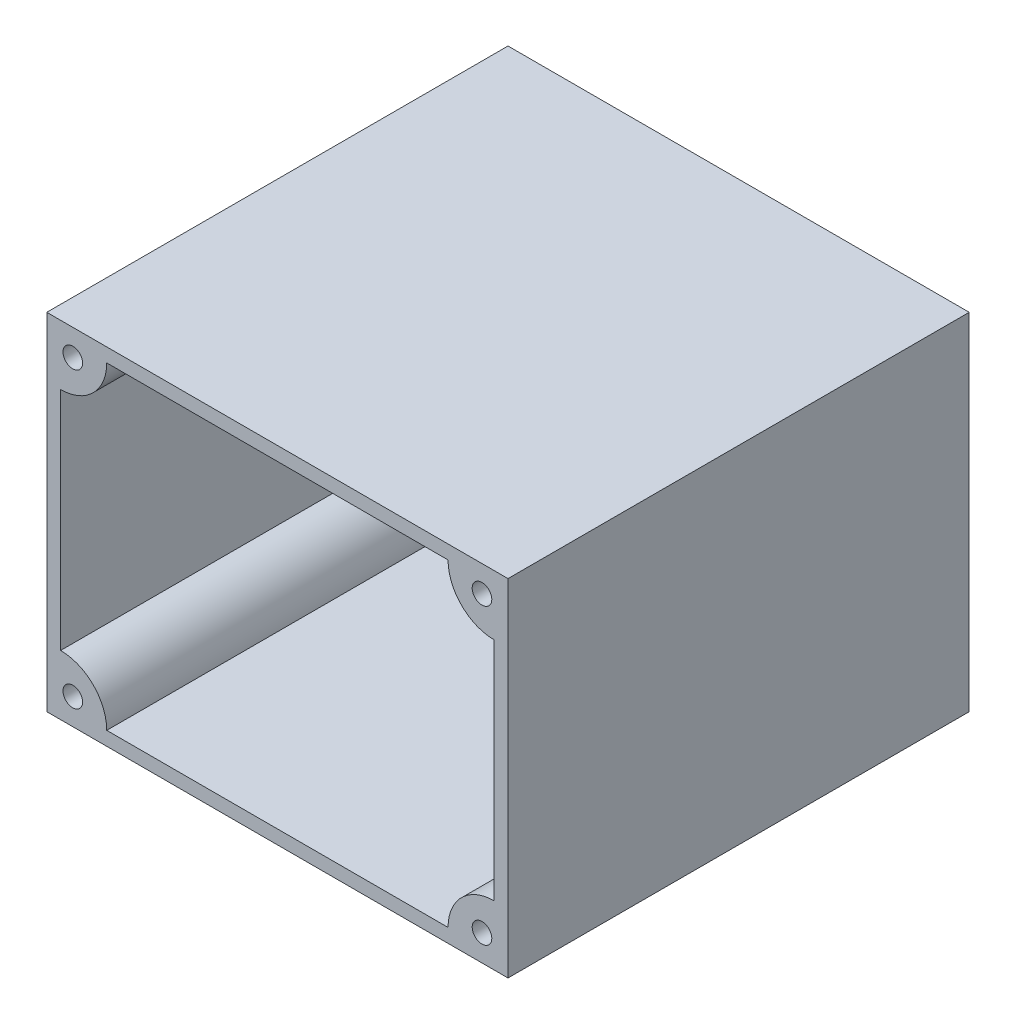
SolidWorks part; units mm, degrees
ref_plane "Plan de face" through (0, 0, 0) normal (0, 0, 1) x (1, 0, 0)
ref_plane "Plan de dessus" through (0, 0, 0) normal (0, 1, 0) x (1, 0, 0)
ref_plane "Plan de droite" through (0, 0, 0) normal (1, 0, 0) x (0, 0, -1)
sketch "Esquisse1" plane through (0, 0, 0) normal (0, 0, 1) x (1, 0, 0)
  line L1 (-40, 30) -> (40, 30)
  line L2 (-40, 30) -> (-40, -30)
  line L3 (-40, -30) -> (40, -30)
  line L4 (40, 30) -> (40, -30)
  line L5 (-40, 30) -> (40, -30) construction
  line L6 (-40, -30) -> (40, 30) construction
  point P0 (0, 0)
  dimension "D1" = 80
  dimension "D2" = 60
extrude "Boss.-Extru.1" add sketch "Esquisse1" along normal blind 80
shell "Coque1" thickness 2.4
sketch "Esquisse2" plane through (0, 0, 80) normal (0, 0, 1) x (1, 0, 0)
  line L0 (-37.6, 27.6) -> (-37.6, 19.6)
  line L1 (-37.6, 27.6) -> (-37.6, -27.6) construction
  line L2 (37.6, 27.6) -> (-37.6, 27.6) construction
  line L3 (-29.6, 27.6) -> (-37.6, 27.6)
  arc A0 (-37.6, 19.6) -> (-29.6, 27.6) centre (-37.6, 27.6) ccw
  dimension "D1" = 8
extrude "Boss.-Extru.2" add sketch "Esquisse2" against normal up to next
hole_wizard "Dégagement M31" positions "Esquisse3" profile "Esquisse4" hole size "M3" standard "ISO"
sketch "Esquisse3" plane through (0, 0, 80) normal (0, 0, 1) x (1, 0, 0)
  point P0 (-35.4882, 25.4607)
sketch "Esquisse4" plane through (-35.4882, 25.4607, 80) normal (1, 0, 0) x (0, -1, 0)
  line L0 (0, 0) -> (0, 11.0215)
  line L1 (0, 11.0215) -> (1.7, 10)
  line L2 (1.7, 10) -> (1.7, 0)
  line L5 (1.7, 0) -> (0, 0)
  line L10 (0, 11.0215) -> (-1.7, 10) construction
  line L11 (0, -6.35) -> (0, 107.95) construction
  dimension "Diamètre du perçage" = 3.4
  dimension "Profondeur du perçage" = 10
  dimension "Angle de pointe" = 118
mirror "Symétrie1" about plane through (0, 0, 0) normal (1, 0, 0) of "Boss.-Extru.2", "Dégagement M31" second plane through (0, 0, 0) second plane normal (0, 1, 0)
equation "\"longueur_ext\"=80"
equation "\"D1@Esquisse1\"=\"longueur_ext\""
equation "\"largeur_ext\"=60"
equation "\"D2@Esquisse1\"=\"largeur_ext\""
equation "\"buse\"= 0.8"
equation "\"couche\"= 0.5"
equation "\"D1@Coque1\"=\"buse\"*3"
